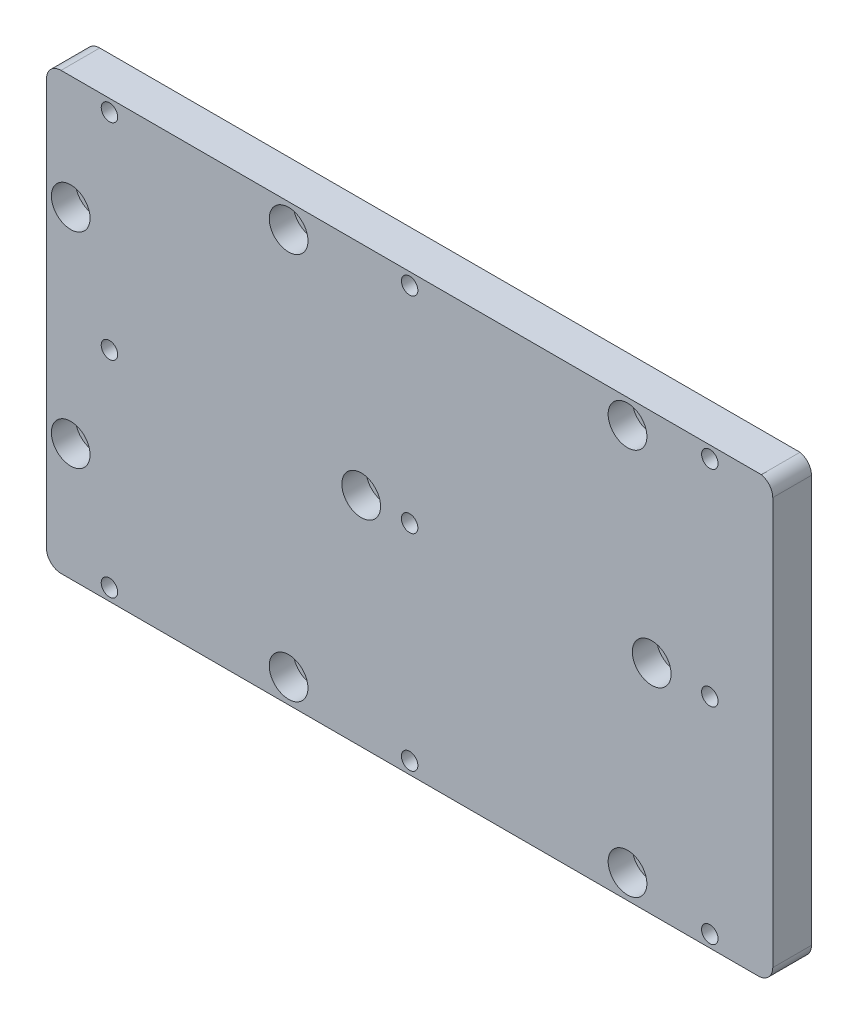
SolidWorks part; units mm, degrees
ref_plane "Plan de face" through (0, 0, 0) normal (0, 0, 1) x (1, 0, 0)
ref_plane "Plan de dessus" through (0, 0, 0) normal (0, 1, 0) x (1, 0, 0)
ref_plane "Plan de droite" through (0, 0, 0) normal (1, 0, 0) x (0, 0, -1)
sketch "Esquisse1" plane through (0, 0, 0) normal (0, 0, 1) x (1, 0, 0)
  line L5 (2.9684, 10.0302) -> (146.9684, 10.0302)
  line L6 (-0.0316, 13.0302) -> (-0.0316, 97.0302)
  line L7 (149.9684, 13.0302) -> (149.9684, 97.0969)
  line L10 (2.9684, 100.0302) -> (147.5976, 100.0302)
  arc A0 (2.9684, 10.0302) -> (-0.0316, 13.0302) centre (2.9684, 13.0302) cw
  arc A1 (146.9684, 10.0302) -> (149.9684, 13.0302) centre (146.9684, 13.0302) ccw
  arc A2 (147.5976, 100.0302) -> (149.9684, 97.0969) centre (146.9684, 97.0969) cw
  arc A3 (-0.0316, 97.0302) -> (2.9684, 100.0302) centre (2.9684, 97.0302) cw
  circle A4 centre (12.9684, 97.5302) radius 1.25
  circle A5 centre (74.9684, 97.5302) radius 1.25
  circle A6 centre (136.9684, 97.5302) radius 1.25
  circle A7 centre (12.9684, 55.0302) radius 1.25
  circle A8 centre (74.9684, 55.0302) radius 1.25
  circle A9 centre (136.9684, 55.0302) radius 1.25
  circle A10 centre (136.9684, 12.5302) radius 1.25
  circle A11 centre (74.9684, 12.5302) radius 1.25
  circle A12 centre (12.9684, 12.5302) radius 1.25
  point P17 (-0.0316, 100.0302)
  dimension "D1" = 3
  dimension "D14" = 85
  dimension "D2" = 13
  dimension "D3" = 13
  dimension "D4" = 75
  dimension "D5" = 13
  dimension "D6" = 75
  dimension "D7" = 13
  dimension "D8" = 2.5
  dimension "D9" = 2.5
  dimension "D10" = 2.5
  dimension "D11" = 13
  dimension "D12" = 75
  dimension "D13" = 13
  dimension "D15" = 2.5
  dimension "D16" = 2.5
  dimension "D17" = 2.5
  dimension "D18" = 150
  dimension "D19" = 90
  dimension "D20" = 75
  dimension "D21" = 45
  dimension "D22" = 45
  dimension "D23" = 45
extrude "Boss.-Extru.1" add sketch "Esquisse1" along normal blind 8
sketch "Esquisse4" plane through (0, 0, 8) normal (0, 0, 1) x (1, 0, 0)
  line L0 (2.9684, 10.0302) -> (146.9684, 10.0302) construction
  line L1 (-0.0316, 97.0302) -> (-0.0316, 13.0302) construction
  line L2 (147.5976, 100.0302) -> (2.9684, 100.0302) construction
  line L3 (149.9684, 13.0302) -> (149.9684, 97.0969) construction
  circle A0 centre (119.9684, 95.0302) radius 1.6
  circle A1 centre (49.9684, 95.0302) radius 1.6
  circle A2 centre (4.9684, 76.5561) radius 1.6
  circle A3 centre (4.9684, 34.2503) radius 1.6
  circle A4 centre (49.9684, 15.0302) radius 1.6
  circle A5 centre (119.9684, 15.0302) radius 1.6
  circle A6 centre (64.9684, 55.0302) radius 1.6
  circle A7 centre (124.9684, 55.0302) radius 1.6
  dimension "D1" = 5
  dimension "D13" = 45
  dimension "D2" = 5
  dimension "D3" = 5
  dimension "D4" = 5
  dimension "D5" = 5
  dimension "D6" = 5
  dimension "D7" = 30
  dimension "D8" = 30
  dimension "D9" = 70
  dimension "D10" = 70
  dimension "D11" = 45
  dimension "D12" = 45
  dimension "D14" = 45
  dimension "D15" = 25
  dimension "D16" = 60
extrude "Enlèv. mat.-Extru.1" cut sketch "Esquisse4" against normal through all
sketch "Esquisse5" plane through (0, 0, 8) normal (0, 0, 1) x (1, 0, 0)
  circle A0 centre (49.9684, 95.0302) radius 4
  circle A1 centre (119.9684, 95.0302) radius 4
  circle A2 centre (124.9684, 55.0302) radius 4
  circle A3 centre (64.9684, 55.0302) radius 4
  circle A4 centre (4.9684, 76.5561) radius 4
  circle A5 centre (4.9684, 34.2503) radius 4
  circle A6 centre (49.9684, 15.0302) radius 4
  circle A7 centre (119.9684, 15.0302) radius 4
extrude "Enlèv. mat.-Extru.2" cut sketch "Esquisse5" against normal blind 5
hole_wizard "Trou taraudé M3" positions "Esquisse9" profile "Esquisse10" hole size "M3" standard "ISO" end condition through all
sketch "Esquisse9" plane through (0, 0, 8) normal (0, 0, 1) x (1, 0, 0)
  point P0 (12.9684, 97.5302)
  point P3 (12.9684, 55.0302)
  point P6 (12.9684, 12.5302)
  point P9 (74.9684, 12.5302)
  point P12 (74.9684, 55.0302)
  point P15 (74.9684, 97.5302)
  point P18 (136.9684, 97.5302)
  point P21 (136.9684, 55.0302)
  point P24 (136.9684, 12.5302)
sketch "Esquisse10" plane through (12.9684, 97.5302, 8) normal (1, 0, 0) x (0, -1, 0)
  line L0 (0, 0) -> (0, 8)
  line L1 (0, 8) -> (1.7, 8)
  line L2 (1.7, 8) -> (1.7, 0)
  line L5 (1.7, 0) -> (0, 0)
  line L11 (0, -6.35) -> (0, 107.95) construction
  dimension "Diamètre du perçage jusqu'au prochain" = 3.4
  dimension "Profondeur du perçage jusqu'au prochain" = 8
